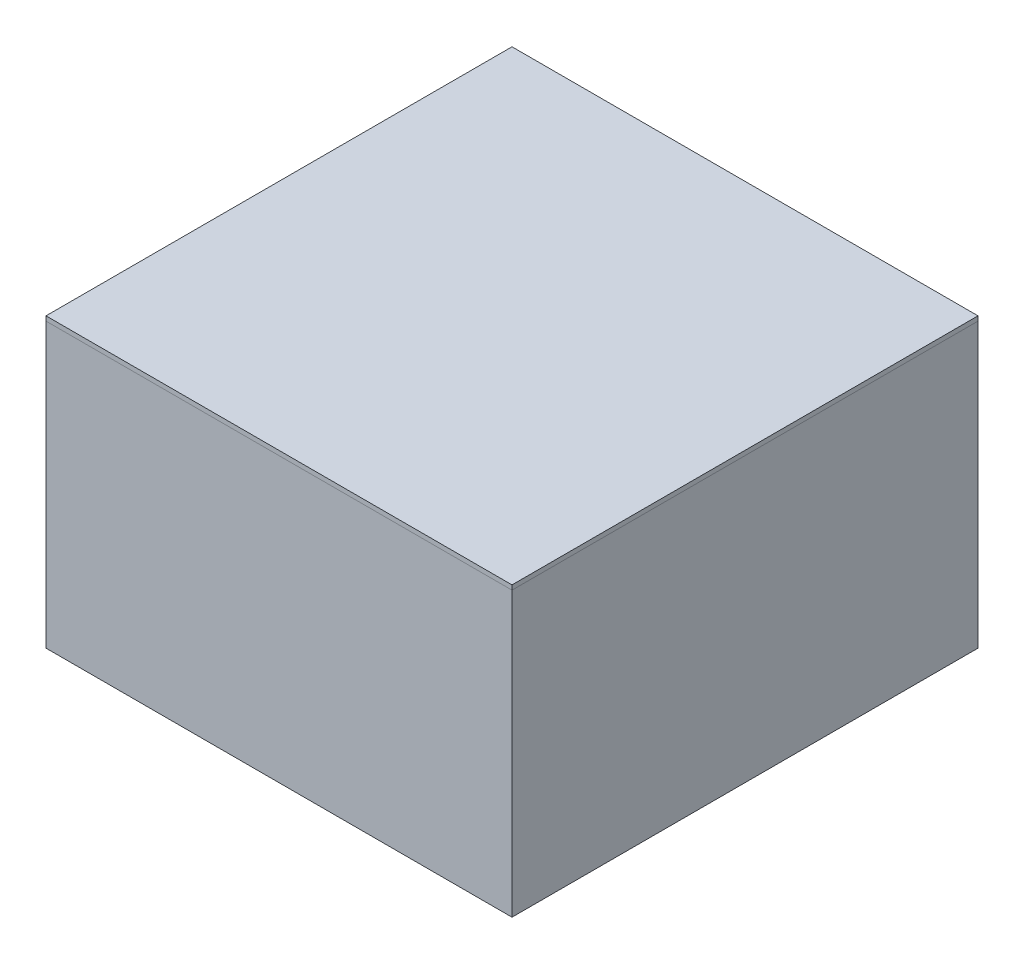
SolidWorks part; units mm, degrees
material "PET"
ref_plane "Front Plane" through (0, 0, 0) normal (0, 0, 1) x (1, 0, 0)
ref_plane "Top Plane" through (0, 0, 0) normal (0, 1, 0) x (1, 0, 0)
ref_plane "Right Plane" through (0, 0, 0) normal (1, 0, 0) x (0, 0, -1)
sketch "Sketch2" plane through (0, 0, 0) normal (0, 1, 0) x (1, 0, 0)
  line L1 (-51, -51) -> (51, -51)
  line L2 (-51, -51) -> (-51, 51)
  line L3 (-51, 51) -> (51, 51)
  line L4 (51, -51) -> (51, 51)
  line L5 (-51, -51) -> (51, 51) construction
  line L6 (-51, 51) -> (51, -51) construction
  point P0 (0, 0)
  dimension "D1" = 102
extrude "Boss-Extrude1" add sketch "Sketch2" along normal mid plane 62
shell "Shell1" thickness 1
sketch "Sketch3" plane through (0, 31, 0) normal (0, 1, 0) x (1, 0, 0)
  line L14 (-49.9, -49.9) -> (49.9, -49.9)
  line L15 (49.9, -49.9) -> (49.9, 49.9)
  line L16 (49.9, 49.9) -> (-49.9, 49.9)
  line L17 (-49.9, 49.9) -> (-49.9, -49.9)
  line L18 (-49.9, -49.9) -> (49.9, -49.9)
  line L19 (49.9, -49.9) -> (49.9, 49.9)
  line L20 (49.9, 49.9) -> (-49.9, 49.9)
  line L21 (-49.9, 49.9) -> (-49.9, -49.9)
  dimension "D1" = 0.1
extrude "Boss-Extrude2" add sketch "Sketch3" against normal blind 1.5 separate body
sketch "Sketch4" plane through (0, 31, 0) normal (0, 1, 0) x (1, 0, 0)
  line L1 (-51, 51) -> (51, 51)
  line L2 (-51, 51) -> (-51, -51)
  line L3 (-51, -51) -> (51, -51)
  line L4 (51, 51) -> (51, -51)
extrude "Boss-Extrude3" add sketch "Sketch4" along normal blind 1
